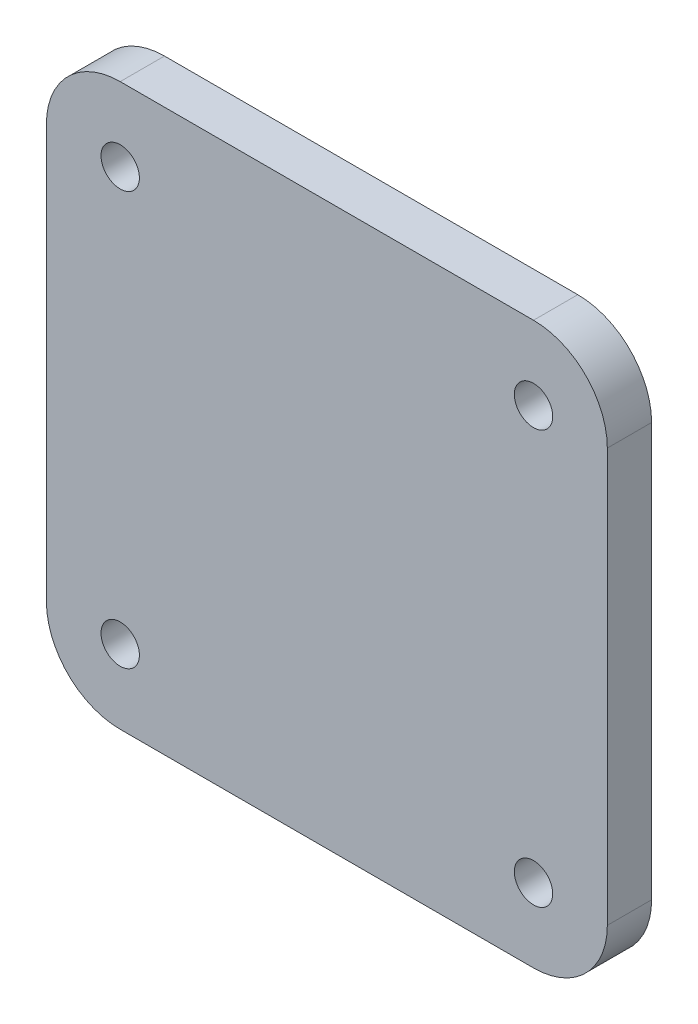
SolidWorks part; units mm, degrees
material "PC 高粘度"
ref_plane "前视基准面" through (0, 0, 0) normal (0, 0, 1) x (1, 0, 0)
ref_plane "上视基准面" through (0, 0, 0) normal (0, 1, 0) x (1, 0, 0)
ref_plane "右视基准面" through (0, 0, 0) normal (1, 0, 0) x (0, 0, -1)
sketch "草图1" plane through (0, 0, 0) normal (0, 0, 1) x (1, 0, 0)
  line L1 (-19, 19) -> (19, 19)
  line L2 (-19, 19) -> (-19, -19)
  line L3 (-19, -19) -> (19, -19)
  line L4 (19, 19) -> (19, -19)
  line L5 (-19, 19) -> (19, -19) construction
  line L6 (-19, -19) -> (19, 19) construction
  line L7 (-14, 14) -> (14, 14) construction
  line L8 (-14, 14) -> (-14, -14) construction
  line L9 (-14, -14) -> (14, -14) construction
  line L10 (14, 14) -> (14, -14) construction
  line L11 (-14, 14) -> (14, -14) construction
  line L12 (-14, -14) -> (14, 14) construction
  circle A0 centre (-14, -14) radius 1.3
  circle A1 centre (14, -14) radius 1.3
  circle A2 centre (14, 14) radius 1.3
  circle A3 centre (-14, 14) radius 1.3
  point P0 (0, 0)
  point P6 (0, 0)
  dimension "D3" = 2.6
  dimension "D1" = 28
  dimension "D2" = 38
extrude "凸台-拉伸1" add sketch "草图1" along normal blind 3
fillet "圆角1" radius 5 4 edges at (19, -19, 1.5) (-19, -19, 1.5) (-19, 19, 1.5) (19, 19, 1.5)
